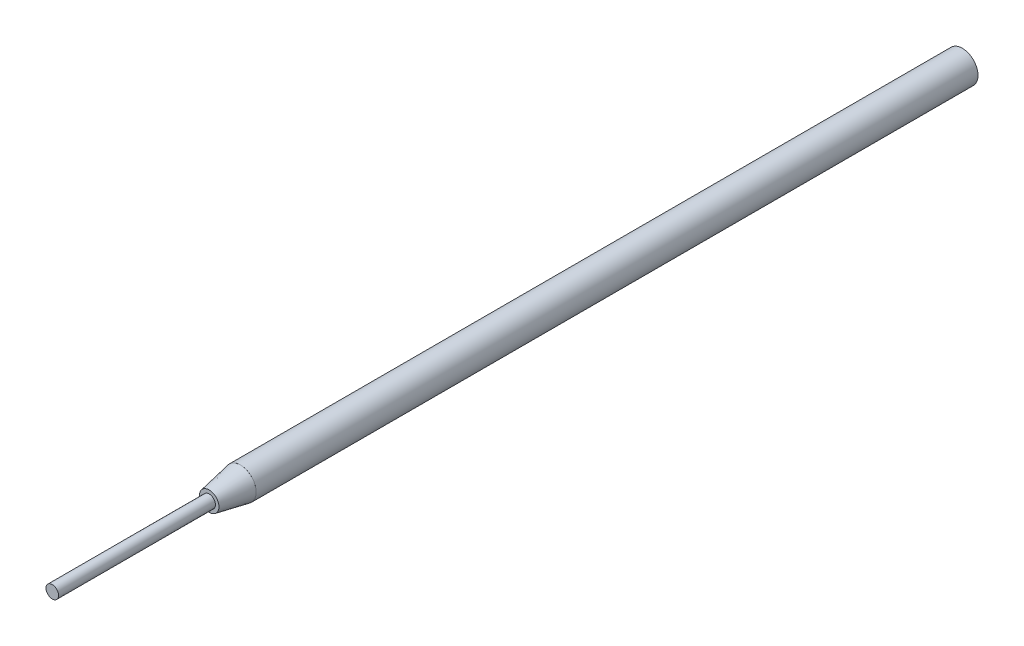
SolidWorks part; units mm, degrees
ref_plane "Front Plane" through (0, 0, 0) normal (0, 0, 1) x (1, 0, 0)
ref_plane "Top Plane" through (0, 0, 0) normal (0, 1, 0) x (1, 0, 0)
ref_plane "Right Plane" through (0, 0, 0) normal (1, 0, 0) x (0, 0, -1)
sketch "Sketch1" plane through (0, 0, 0) normal (0, 0, 1) x (1, 0, 0)
  circle A0 centre (0, 0) radius 2.5
  dimension "D1" = 5
extrude "Boss-Extrude1" add sketch "Sketch1" along normal blind 115
sketch "Sketch2" plane through (0, 0, 0) normal (0, 1, 0) x (1, 0, 0)
  line L0 (0, 0) -> (0, -50000) construction
  line L1 (-1.9471, -115.0071) -> (-1, -119.9862)
  line L2 (-1, -119.9862) -> (-1.5529, -119.9862)
  line L3 (-1.5529, -119.9862) -> (-2.5, -115.0071)
  line L4 (-2.5, -115.0071) -> (-1.9471, -115.0071)
  line L5 (-2.5, -115.0071) -> (-6.6362, -115.0071) construction
  line L6 (-1.5529, -119.9862) -> (-6.9049, -119.9862) construction
  point P5 (0, 0)
  point P10 (-1.3106, -119.9862)
  dimension "D2" = 2.5
revolve "Revolve1" add sketch "Sketch2" angle 360 about L0
sketch "Sketch3" plane through (0, 0, 0) normal (0, 1, 0) x (1, 0, 0)
  line L0 (0, 0) -> (0, -50000) construction
  point P7 (0.9625, -135.0675)
  point P13 (5.8665, -138.1189)
sketch "Sketch4" plane through (0, 0, 119.9862) normal (0, 0, 1) x (1, 0, 0)
  circle A1 centre (0, 0) radius 1.5529
  circle A2 centre (0, 0) radius 1.5529
  circle M2 centre (0, 0) radius 1
  dimension "D1" = 0
extrude "Boss-Extrude2" add sketch "Sketch4" along normal blind 25 separate body contours M2
